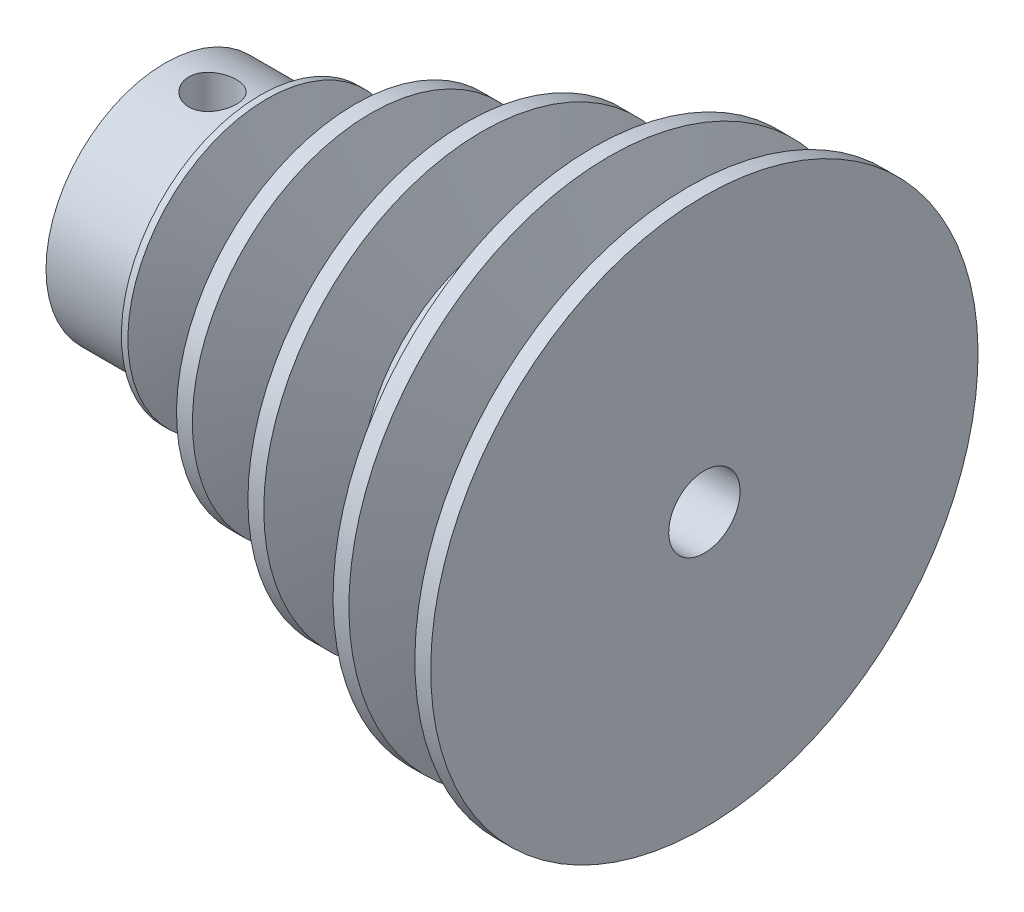
SolidWorks part; units mm, degrees
ref_plane "Front Plane" through (0, 0, 0) normal (0, 0, 1) x (1, 0, 0)
ref_plane "Top Plane" through (0, 0, 0) normal (0, 1, 0) x (1, 0, 0)
ref_plane "Right Plane" through (0, 0, 0) normal (1, 0, 0) x (0, 0, -1)
sketch "Sketch2" plane through (0, 0, 0) normal (0, 0, 1) x (1, 0, 0)
  line L0 (0, -4.5) -> (0, 5.7733) construction
  line L1 (0, 1.2393) -> (-9.7266, 1.2393) construction
  line L2 (0, 5.7393) -> (68, 5.7393)
  line L3 (68, 5.7393) -> (68, 35.7393)
  line L4 (68, 35.7393) -> (66, 35.7393)
  line L5 (66, 35.7393) -> (62.3603, 25.7393)
  line L6 (62.3603, 25.7393) -> (58.9938, 25.7393)
  line L7 (58.9938, 25.7393) -> (55.9758, 34.0312)
  line L8 (55.9758, 34.0312) -> (53.9758, 34.0312)
  line L9 (53.9758, 34.0312) -> (53.9758, 26.3077)
  line L10 (53.9758, 26.3077) -> (51.62, 26.3077)
  line L11 (51.62, 26.3077) -> (49.2293, 19.7393)
  line L12 (49.2293, 19.7393) -> (43.2293, 19.7393)
  line L13 (43.2293, 19.7393) -> (39.9535, 28.7393)
  line L14 (39.9535, 28.7393) -> (37.9535, 28.7393)
  line L15 (37.9535, 28.7393) -> (37.9535, 19.6624)
  line L16 (37.9535, 19.6624) -> (34.5881, 19.6624)
  line L17 (34.5881, 19.6624) -> (32.4322, 13.7393)
  line L18 (32.4322, 13.7393) -> (29.5932, 13.7393)
  line L19 (29.5932, 13.7393) -> (25.9535, 23.7393)
  line L20 (25.9535, 23.7393) -> (23.9535, 23.7393)
  line L21 (23.9535, 23.7393) -> (23.9535, 21.2393)
  line L22 (23.9535, 21.2393) -> (22.9014, 21.2393)
  line L23 (22.9014, 21.2393) -> (18.8977, 10.2393)
  line L24 (18.8977, 10.2393) -> (15.9144, 10.2393)
  line L25 (15.9144, 10.2393) -> (12.8207, 18.7393)
  line L26 (12.8207, 18.7393) -> (12, 18.7393)
  line L27 (12, 18.7393) -> (12, 16.2393)
  line L28 (12, 16.2393) -> (0, 16.2393)
  line L29 (0, 16.2393) -> (0, 5.7393)
  line L30 (60.677, 25.7393) -> (60.677, 29.8266) construction
  point P2 (17.4061, 10.2393)
  point P5 (16.0101, 7.139)
  point P36 (14.226, 15.1737)
  point P37 (18.818, 6.9907)
  point P38 (24.9132, 22.7317)
  point P39 (51.9867, 26.3077)
  point P40 (55.9758, 34.0312)
  point P41 (15.9144, 10.2393)
  point P42 (0, 0)
  dimension "D1" = 2
  dimension "D2" = 2
  dimension "D3" = 2
  dimension "D4" = 2
  dimension "D5" = 40
  dimension "D6" = 20
  dimension "D7" = 12
  dimension "D8" = 15
  dimension "D9" = 17.5
  dimension "D10" = 22.5
  dimension "D11" = 27.5
  dimension "D12" = 34.5
  dimension "D13" = 68
  dimension "D14" = 6
  dimension "D15" = 14
  dimension "D16" = 4.5
  dimension "D17" = 18.5
  dimension "D18" = 9
  dimension "D19" = 12.5
  dimension "D20" = 24.5
  dimension "D21" = 2.5
revolve "Revolve1" add sketch "Sketch2" angle 360 about L1
sketch "Sketch3" plane through (0, 0, 0) normal (0, 1, 0) x (1, 0, 0)
  line L0 (0, 15) -> (0, -15) construction
  circle A0 centre (6, 0) radius 3
  dimension "D2" = 6
  dimension "D1" = 6
extrude "Cut-Extrude1" cut sketch "Sketch3" along normal blind 24 contours A0
